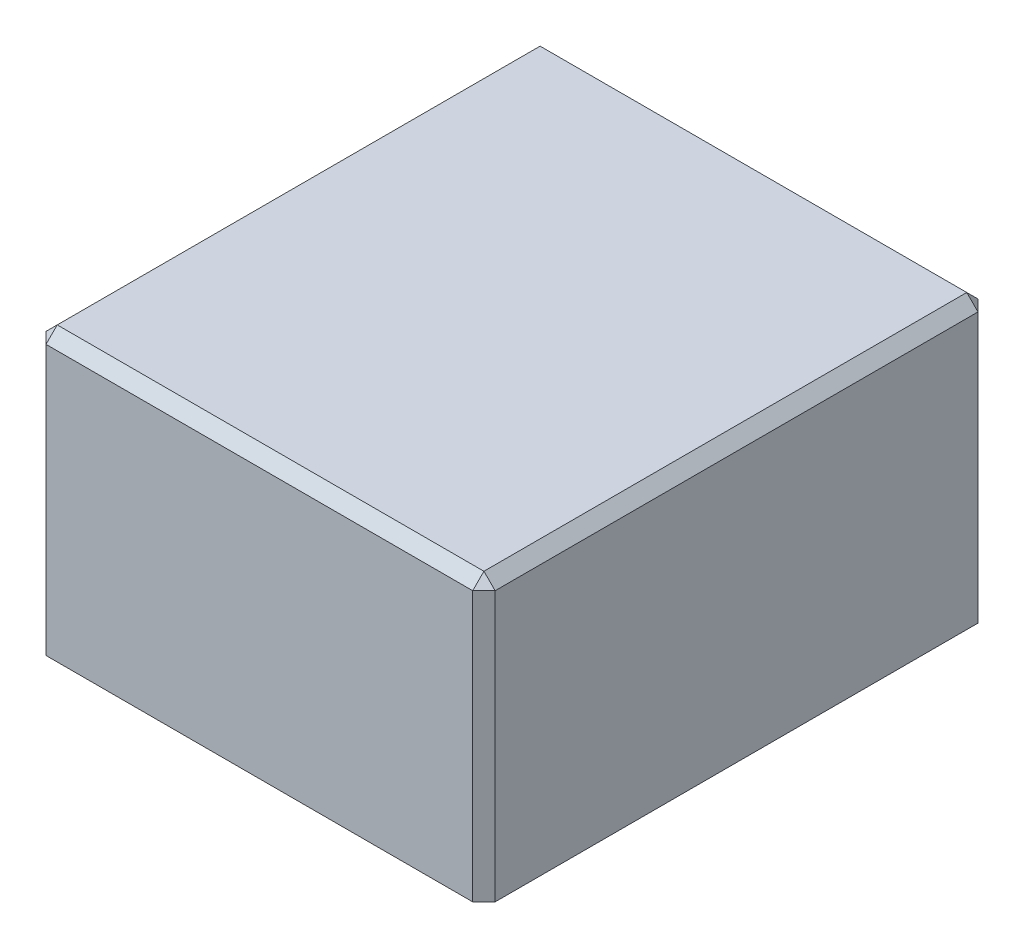
SolidWorks part; units mm, degrees
ref_plane "Front Plane" through (0, 0, 0) normal (0, 0, 1) x (1, 0, 0)
ref_plane "Top Plane" through (0, 0, 0) normal (0, 1, 0) x (1, 0, 0)
ref_plane "Right Plane" through (0, 0, 0) normal (1, 0, 0) x (0, 0, -1)
sketch "Sketch1" plane through (0, 0, 0) normal (0, 1, 0) x (1, 0, 0)
  line L0 (-2, 2.25) -> (2, 2.25)
  line L1 (-1.5, -1.75) -> (1.5, -1.75) construction
  line L2 (-1.5, -1.75) -> (-1.5, 1.75) construction
  line L3 (-1.5, 1.75) -> (1.5, 1.75) construction
  line L4 (1.5, -1.75) -> (1.5, 1.75) construction
  line L5 (-1.5, -1.75) -> (1.5, 1.75) construction
  line L6 (-1.5, 1.75) -> (1.5, -1.75) construction
  line L7 (2, -2.25) -> (2, 2.25)
  line L8 (-2, -2.25) -> (2, -2.25)
  line L9 (-2, -2.25) -> (-2, 2.25)
  line L10 (1.6, -1.85) -> (1.6, 1.85)
  line L11 (-1.6, 1.85) -> (1.6, 1.85)
  line L12 (-1.6, -1.85) -> (-1.6, 1.85)
  line L13 (-1.6, -1.85) -> (1.6, -1.85)
  point P0 (0, 0)
  dimension "D1" = 3
  dimension "D2" = 3.5
  dimension "D3" = 0.5
  dimension "D4" = 0.1
extrude "Boss-Extrude1" add sketch "Sketch1" along normal blind 0.5
sketch "Sketch2" plane through (0, 0.5, 0) normal (0, 1, 0) x (1, 0, 0)
  line L8 (-2, 2.25) -> (-2, -2.25)
  line L9 (-2, -2.25) -> (2, -2.25)
  line L10 (2, -2.25) -> (2, 2.25)
  line L11 (2, 2.25) -> (-2, 2.25)
  line L12 (-2, 2.25) -> (-2, -2.25)
  line L13 (-2, -2.25) -> (2, -2.25)
  line L14 (2, -2.25) -> (2, 2.25)
  line L15 (2, 2.25) -> (-2, 2.25)
  dimension "D1" = 0
extrude "Boss-Extrude2" add sketch "Sketch2" along normal blind 2
chamfer "Chamfer1" distance 0.1 angle 45 8 edges at (2, 1.25, -2.25) (-2, 1.25, -2.25) (-2, 1.25, 2.25) (0, 2.5, -2.25) (-2, 2.5, 0) (0, 2.5, 2.25) (2, 2.5, 0) (2, 1.25, 2.25)
